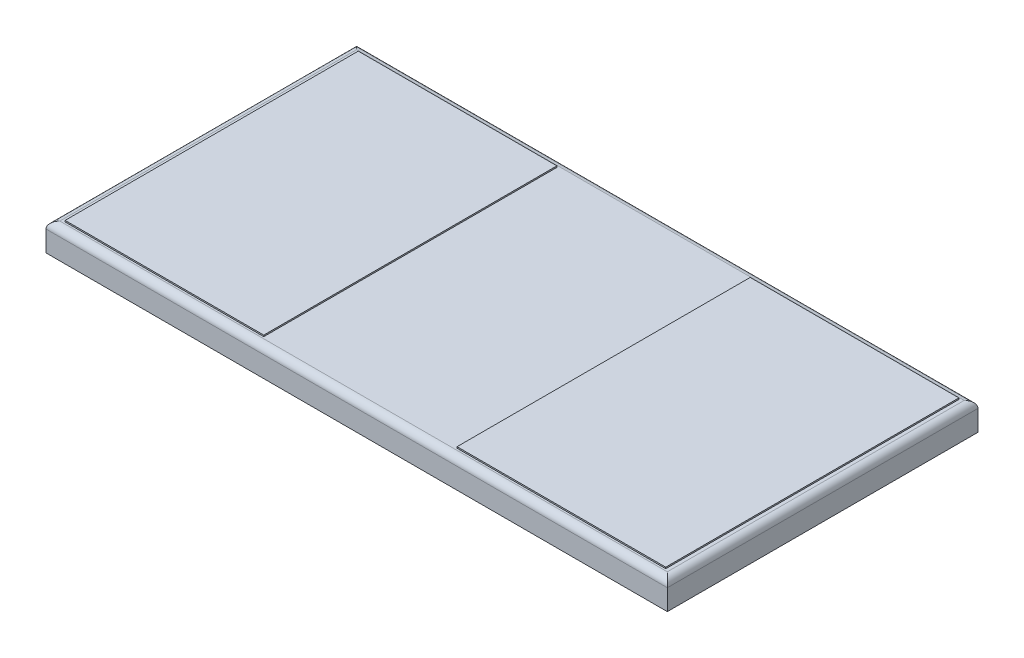
SolidWorks part; units mm, degrees
ref_plane "Front Plane" through (0, 0, 0) normal (0, 0, 1) x (1, 0, 0)
ref_plane "Top Plane" through (0, 0, 0) normal (0, 1, 0) x (1, 0, 0)
ref_plane "Right Plane" through (0, 0, 0) normal (1, 0, 0) x (0, 0, -1)
sketch "Sketch1" plane through (0, 0, 0) normal (0, 1, 0) x (1, 0, 0)
  line L1 (0, 0) -> (2286, 0)
  line L2 (0, 0) -> (0, 1143)
  line L3 (0, 1143) -> (2286, 1143)
  line L4 (2286, 0) -> (2286, 1143)
  dimension "D1" = 2286
  dimension "D2" = 1143
extrude "Boss-Extrude1" add sketch "Sketch1" along normal blind 101.6
sketch "Sketch2" plane through (0, 101.6, 0) normal (0, 1, 0) x (1, 0, 0)
  line L0 (0, 1143) -> (0, 0) construction
  line L1 (38.1, 1110.722) -> (769.0159, 1110.722)
  line L2 (38.1, 1110.722) -> (38.1, 32.215)
  line L3 (38.1, 32.215) -> (769.0159, 32.215)
  line L4 (769.0159, 1110.722) -> (769.0159, 32.215)
  line L5 (1480.2159, 1110.722) -> (2247.9, 1110.722)
  line L6 (1480.2159, 1110.722) -> (1480.2159, 32.215)
  line L7 (1480.2159, 32.215) -> (2247.9, 32.215)
  line L8 (2247.9, 1110.722) -> (2247.9, 32.215)
  line L9 (2286, 0) -> (2286, 1143) construction
  dimension "D1" = 711.2
  dimension "D2" = 38.1
  dimension "D3" = 38.1
extrude "Cut-Extrude1" cut sketch "Sketch2" against normal blind 88.9
sketch "Sketch3" plane through (0, 12.7, 0) normal (0, 1, 0) x (1, 0, 0)
  line L1 (38.1, 1110.722) -> (769.0159, 1110.722)
  line L2 (38.1, 1110.722) -> (38.1, 32.215)
  line L3 (38.1, 32.215) -> (769.0159, 32.215)
  line L4 (769.0159, 1110.722) -> (769.0159, 32.215)
  line L5 (1480.2159, 1110.722) -> (2247.9, 1110.722)
  line L6 (1480.2159, 1110.722) -> (1480.2159, 32.215)
  line L7 (1480.2159, 32.215) -> (2247.9, 32.215)
  line L8 (2247.9, 1110.722) -> (2247.9, 32.215)
extrude "Boss-Extrude2" add sketch "Sketch3" along normal blind 93.98
fillet "Fillet1" radius 25.4 4 edges at (1143, 101.6, 0) (2286, 101.6, -571.5) (1143, 101.6, -1143) (0, 101.6, -571.5)
